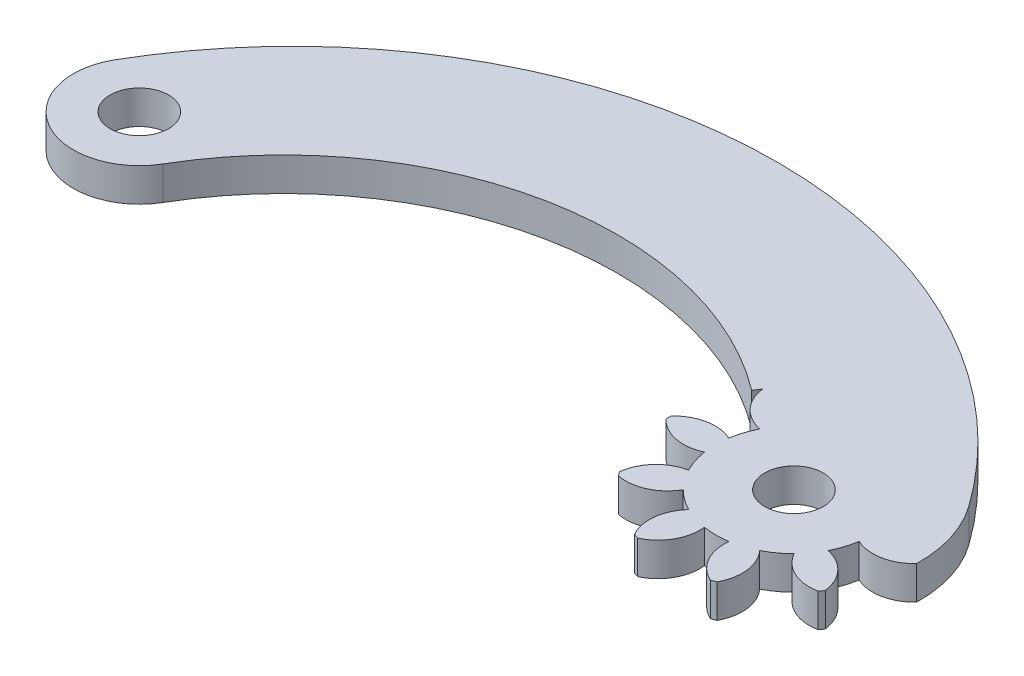
SolidWorks part; units mm, degrees
ref_plane "Front Plane" through (0, 0, 0) normal (0, 0, 1) x (1, 0, 0)
ref_plane "Top Plane" through (0, 0, 0) normal (0, 1, 0) x (1, 0, 0)
ref_plane "Right Plane" through (0, 0, 0) normal (1, 0, 0) x (0, 0, -1)
sketch "Sketch1" plane through (0, 0, 0) normal (0, 1, 0) x (1, 0, 0)
  line L0 (0, 25.5178) -> (0, -32.2544) construction
  line L1 (0, 0) -> (39.1784, 0) construction
  arc A0 (-3.4215, 1.9738) -> (3.4127, -1.989) centre (0, 0) ccw
  arc A3 (-3.4215, 1.9738) -> (45.2762, 4.3666) centre (21.6982, -12.5177) cw
  circle A4 centre (0, 0) radius 1.75
  circle A5 centre (39.1784, 0) radius 1.75
  arc A8 (32.7638, 3.8863) -> (45.2762, 4.3666) centre (39.1784, 0) ccw
  arc A9 (3.4127, -1.989) -> (32.7638, 3.8863) centre (20.6922, -12.0597) cw
  dimension "D2" = 7.9
  dimension "D3" = 15
  dimension "D4" = 29
  dimension "D5" = 20
  dimension "D6" = 3.5
  dimension "D7" = 3.5
  dimension "D1" = 39.1784
extrude "Boss-Extrude1" add sketch "Sketch1" along normal mid plane 2
sketch "Sketch8" plane through (0, 1, 0) normal (0, 1, 0) x (1, 0, 0)
  arc A16 (33.0216, 4.2829) -> (35.0048, 2.1317) centre (35.5037, 4.5814) ccw
  arc A17 (35.0048, 2.1317) -> (34.5489, 0.7286) centre (39.1784, 0) ccw
  arc A18 (34.5489, 0.7286) -> (31.68, 0.1539) centre (33.5126, -1.5465) ccw
  arc A20 (31.68, -0.1539) -> (34.5489, -0.7286) centre (33.5126, 1.5465) ccw
  arc A21 (34.5489, -0.7286) -> (35.0048, -2.1317) centre (39.1784, 0) ccw
  arc A22 (35.0048, -2.1317) -> (33.0216, -4.2829) centre (35.5037, -4.5814) ccw
  arc A24 (33.2025, -4.532) -> (35.8613, -3.3106) centre (33.6857, -2.0791) ccw
  arc A25 (35.8613, -3.3106) -> (37.0549, -4.1778) centre (39.1784, 0) ccw
  arc A26 (37.0549, -4.1778) -> (36.7149, -7.0839) centre (38.8984, -5.8664) ccw
  arc A28 (37.0077, -7.179) -> (38.4407, -4.6281) centre (35.9567, -4.9106) ccw
  arc A29 (38.4407, -4.6281) -> (39.9161, -4.6281) centre (39.1784, 0) ccw
  arc A30 (39.9161, -4.6281) -> (41.3492, -7.179) centre (42.4001, -4.9106) ccw
  arc A32 (41.6419, -7.0839) -> (41.3019, -4.1778) centre (39.4584, -5.8664) ccw
  arc A33 (41.3019, -4.1778) -> (42.4955, -3.3106) centre (39.1784, 0) ccw
  arc A34 (42.4955, -3.3106) -> (45.1543, -4.532) centre (44.6712, -2.0791) ccw
  arc A36 (45.3352, -4.2829) -> (43.352, -2.1317) centre (42.8531, -4.5814) ccw
  arc A37 (43.352, -2.1317) -> (43.8079, -0.7286) centre (39.1784, 0) ccw
  arc A38 (43.8079, -0.7286) -> (46.6768, -0.1539) centre (44.8442, 1.5465) ccw
  circle A40 centre (39.1784, 0) radius 1.75 construction
  circle A41 centre (39.1784, 0) radius 1.75 construction
  arc A42 (33.0216, 4.2829) -> (31.68, 0.1539) centre (39.1784, 0) ccw
  arc A46 (31.68, -0.1539) -> (33.0216, -4.2829) centre (39.1784, 0) ccw
  arc A47 (33.2025, -4.532) -> (36.7149, -7.0839) centre (39.1784, 0) ccw
  arc A48 (37.0077, -7.179) -> (41.3492, -7.179) centre (39.1784, 0) ccw
  arc A49 (41.6419, -7.0839) -> (45.1543, -4.532) centre (39.1784, 0) ccw
  arc A50 (45.3352, -4.2829) -> (46.6768, -0.1539) centre (39.1784, 0) ccw
  dimension "D1" = 15
extrude "Cut-Extrude2" cut sketch "Sketch8" against normal through all
